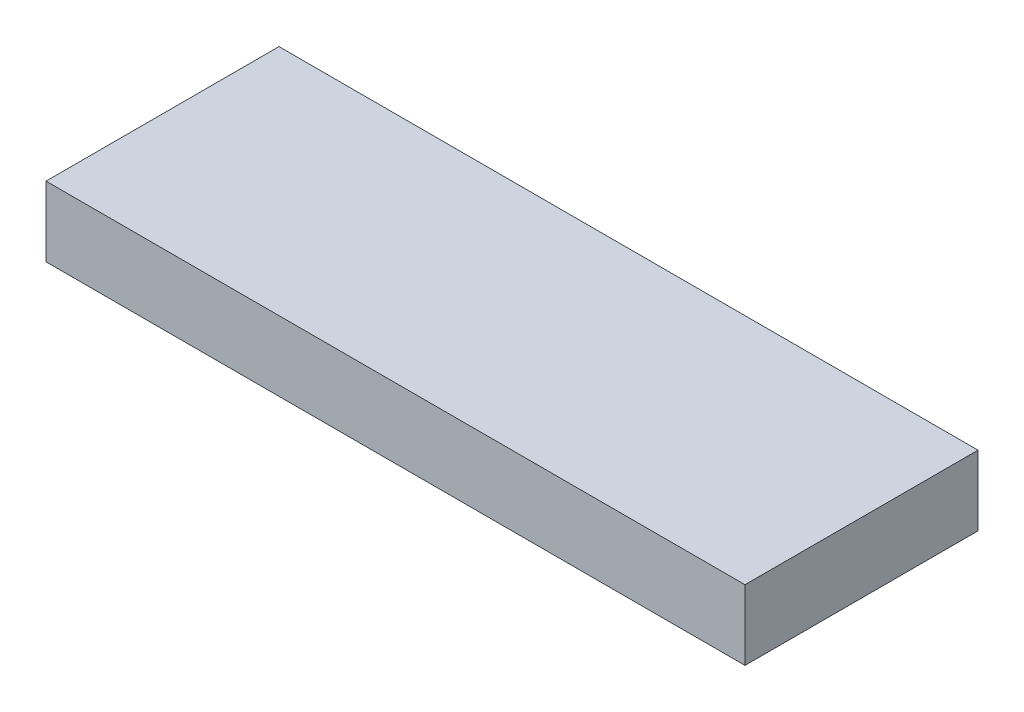
SolidWorks part; units mm, degrees
ref_plane "Front Plane" through (0, 0, 0) normal (0, 0, 1) x (1, 0, 0)
ref_plane "Top Plane" through (0, 0, 0) normal (0, 1, 0) x (1, 0, 0)
ref_plane "Right Plane" through (0, 0, 0) normal (1, 0, 0) x (0, 0, -1)
sketch "Sketch1" plane through (0, 0, 0) normal (0, 1, 0) x (1, 0, 0)
  line L1 (-75, -25) -> (75, -25)
  line L2 (-75, -25) -> (-75, 25)
  line L3 (-75, 25) -> (75, 25)
  line L4 (75, -25) -> (75, 25)
  line L5 (-75, -25) -> (75, 25) construction
  line L6 (-75, 25) -> (75, -25) construction
  point P0 (0, 0)
  dimension "D1" = 150
  dimension "D2" = 50
extrude "Boss-Extrude1" add sketch "Sketch1" along normal mid plane 15
